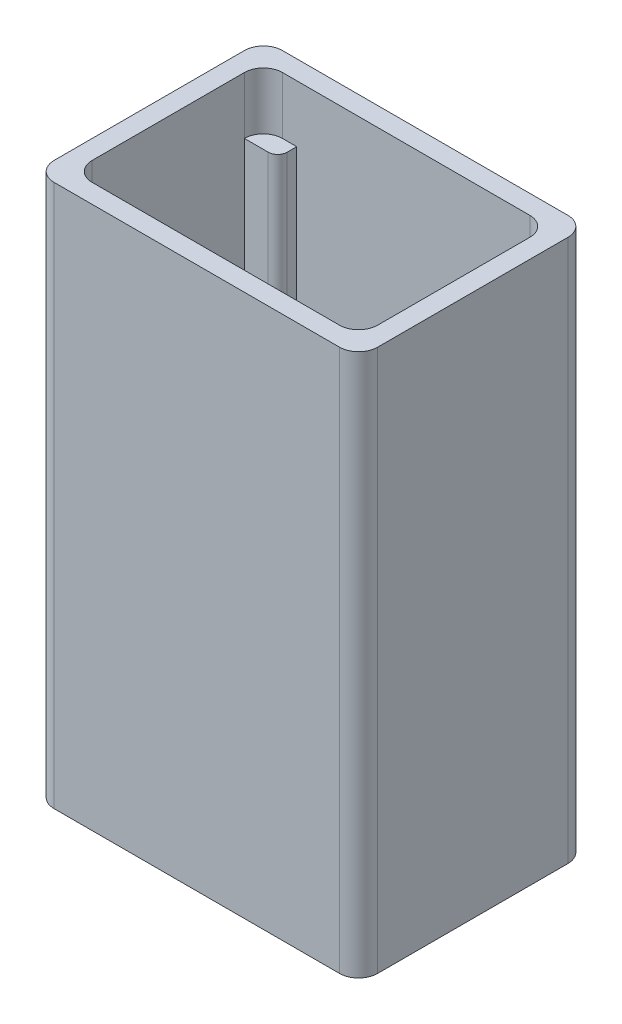
SolidWorks part; units mm, degrees
ref_plane "Front Plane" through (0, 0, 0) normal (0, 0, 1) x (1, 0, 0)
ref_plane "Top Plane" through (0, 0, 0) normal (0, 1, 0) x (1, 0, 0)
ref_plane "Right Plane" through (0, 0, 0) normal (1, 0, 0) x (0, 0, -1)
ref_plane "Plane1" through (0, 58, 0) normal (0, 1, 0) x (1, 0, 0)
sketch "Sketch8" plane through (0, 58, 0) normal (0, 1, 0) x (1, 0, 0)
  line L0 (-13, -10) -> (13, -10)
  line L1 (-15, -8) -> (-15, 8)
  line L2 (-13, 10) -> (13, 10)
  line L3 (15, -8) -> (15, 8)
  line L5 (-15, 10) -> (15, -10) construction
  line L6 (-15, -12) -> (15, -12)
  line L7 (-17, -10) -> (-17, 10)
  line L8 (-15, 12) -> (15, 12)
  line L9 (17, -10) -> (17, 10)
  line L11 (-17, 12) -> (17, -12) construction
  line L15 (0, 12) -> (0, -10) construction
  arc A0 (15, -8) -> (13, -10) centre (13, -8) cw
  arc A1 (-15, -8) -> (-13, -10) centre (-13, -8) ccw
  arc A4 (17, -10) -> (15, -12) centre (15, -10) cw
  arc A5 (-17, -10) -> (-15, -12) centre (-15, -10) ccw
  arc A6 (15, 12) -> (17, 10) centre (15, 10) cw
  arc A7 (-15, 12) -> (-17, 10) centre (-15, 10) ccw
  arc A8 (-13, 10) -> (-15, 8) centre (-13, 8) ccw
  arc A9 (13, 10) -> (15, 8) centre (13, 8) cw
  point P0 (0, 0)
  point P19 (-15, 10)
  point P26 (0, 0)
  point P27 (-12, 9.5)
  point P28 (15, 10)
  dimension "D3" = 2
  dimension "D6" = 2
  dimension "D2" = 34
  dimension "D7" = 2
  dimension "D1" = 30
  dimension "D4" = 24
  dimension "D5" = 20
sketch "Sketch11" plane through (0, 58, 0) normal (0, 1, 0) x (1, 0, 0)
  line L8 (15, 8) -> (12.5, 8)
  line L9 (11.5, 9) -> (11.5, 10)
  line L10 (-13, 10) -> (13, 10) construction
  line L11 (11.5, 10) -> (15, 10)
  line L12 (15, 10) -> (15, 8)
  line L13 (0, 12) -> (0, -10) construction
  line L14 (0, 12) -> (0, -10) construction
  line L15 (-11.5, 10) -> (-15, 10)
  line L16 (-11.5, 9) -> (-11.5, 10)
  line L17 (-15, 8) -> (-12.5, 8)
  line L18 (-15, 10) -> (-15, 8)
  arc A2 (12.5, 8) -> (11.5, 9) centre (12.5, 9) cw
  arc A3 (-12.5, 8) -> (-11.5, 9) centre (-12.5, 9) ccw
  dimension "D1" = 11.5
  dimension "D2" = 1
extrude "Boss-Extrude4" add sketch "Sketch8" along normal blind 57
extrude "Boss-Extrude5" add sketch "Sketch11" along normal blind 51
